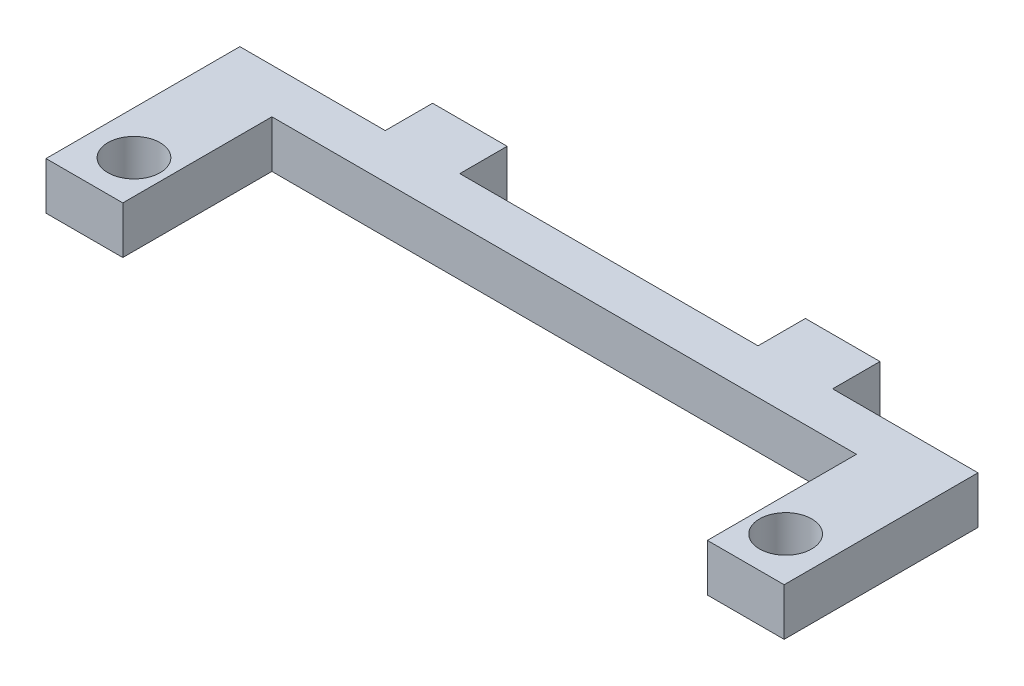
SolidWorks part; units mm, degrees
ref_plane "Front Plane" through (0, 0, 0) normal (0, 0, 1) x (1, 0, 0)
ref_plane "Top Plane" through (0, 0, 0) normal (0, 1, 0) x (1, 0, 0)
ref_plane "Right Plane" through (0, 0, 0) normal (1, 0, 0) x (0, 0, -1)
sketch "Sketch1" plane through (0, 0, 0) normal (0, 1, 0) x (1, 0, 0)
  line L0 (-24.75, 0) -> (24.75, 0) construction
  line L1 (-24.75, -10) -> (24.75, -10) construction
  line L2 (-24.75, -3) -> (-24.75, 10)
  line L3 (-24.75, 10) -> (-15, 10)
  line L4 (24.75, -3) -> (24.75, 10)
  line L5 (-24.75, -10) -> (24.75, 10) construction
  line L6 (-24.75, 10) -> (24.75, -10) construction
  line L7 (-24.75, -3) -> (-19.6, -3)
  line L8 (-19.6, -3) -> (-19.6, 7)
  line L9 (-19.6, 7) -> (19.6, 7)
  line L10 (19.6, 7) -> (19.6, -3)
  line L11 (19.6, -3) -> (24.75, -3)
  line L12 (24.75, -10) -> (24.75, -3) construction
  line L13 (-24.75, -10) -> (-24.75, -3) construction
  line L14 (0, 0) -> (0, 10) construction
  line L15 (15, 10) -> (24.75, 10)
  line L16 (-15, 10) -> (-15, 13.175)
  line L17 (-15, 13.175) -> (-10, 13.175)
  line L18 (-10, 10) -> (-10, 13.175)
  line L20 (10, 10) -> (10, 13.175)
  line L21 (10, 13.175) -> (15, 13.175)
  line L22 (15, 10) -> (15, 13.175)
  line L23 (0, 10) -> (-10, 10) construction
  line L24 (0, 10) -> (0, 13.175) construction
  line L25 (0, 13.175) -> (10, 13.175) construction
  line L26 (0, 13.175) -> (-10, 13.175) construction
  line L27 (-10, 10) -> (10, 10)
  circle A0 centre (-21.85, 0) radius 1.75
  circle A1 centre (21.85, 0) radius 1.75
  point P0 (0, 0)
  point P12 (-23.6, 0)
  point P13 (23.6, 0)
  point P16 (-20.1, 0)
  point P31 (0, 7)
  dimension "D3" = 3.5
  dimension "D1" = 49.5
  dimension "D2" = 20
  dimension "D4" = 10
  dimension "D5" = 1.15
  dimension "D6" = 1.15
  dimension "D7" = 0.5
  dimension "D8" = 3.175
  dimension "D9" = 5
  dimension "D10" = 5
  dimension "D11" = 10
  dimension "D12" = 3
  dimension "D13" = 3
extrude "Boss-Extrude1" add sketch "Sketch1" along normal blind 3.175
